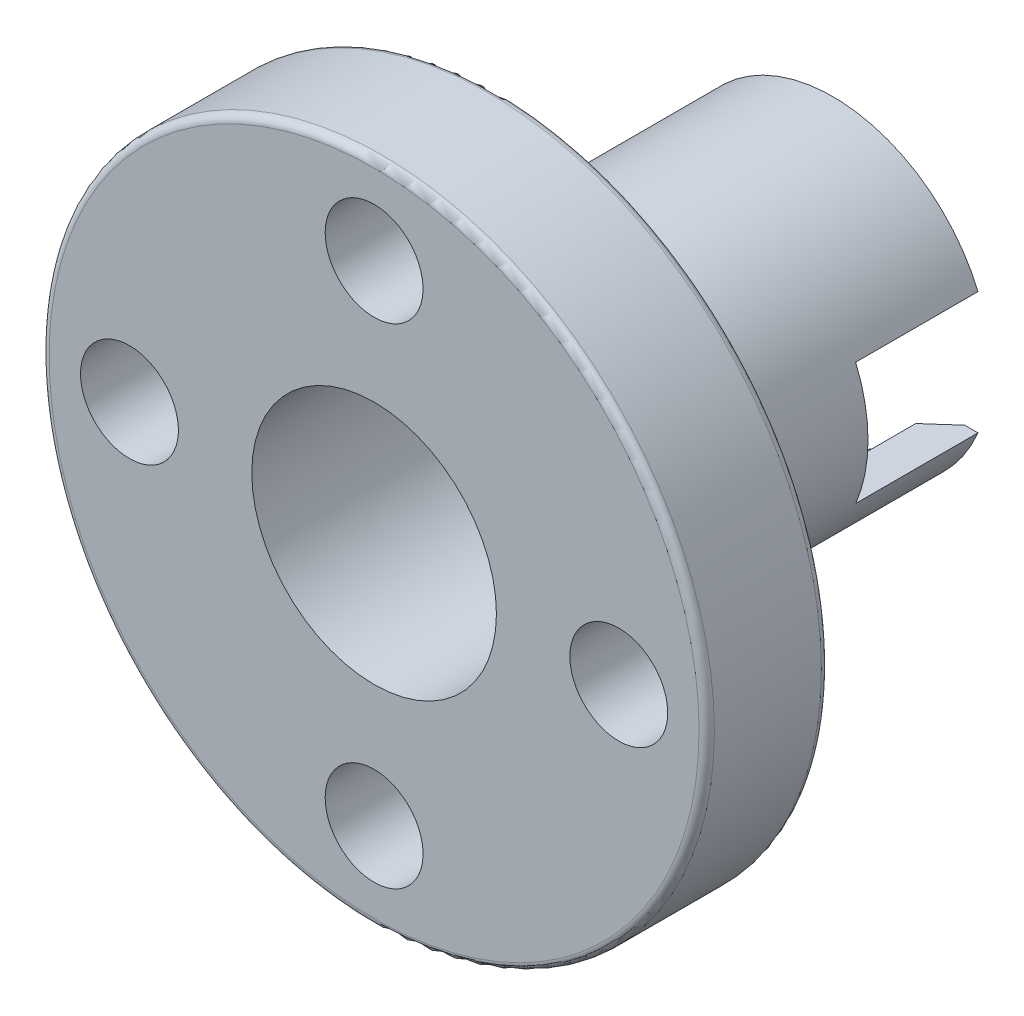
SolidWorks part; units mm, degrees
material "Brass"
ref_plane "Front Plane" through (0, 0, 0) normal (0, 0, 1) x (1, 0, 0)
ref_plane "Top Plane" through (0, 0, 0) normal (0, 1, 0) x (1, 0, 0)
ref_plane "Right Plane" through (0, 0, 0) normal (1, 0, 0) x (0, 0, -1)
sketch "Sketch1" plane through (0, 0, 0) normal (0, 1, 0) x (1, 0, 0)
  line L0 (0, 0) -> (-10.875, 0)
  line L1 (-10.875, 0) -> (-10.875, 4)
  line L2 (-10.875, 4) -> (-5.15, 4)
  line L3 (-5.15, 4) -> (-5.15, 15)
  line L4 (-5.15, 15) -> (0, 15)
  line L5 (0, 15) -> (0, 0)
  dimension "D1" = 10.875
  dimension "D2" = 5.15
  dimension "D3" = 4
  dimension "D4" = 15
revolve "Revolve1" add sketch "Sketch1" angle 360 about L5
sketch "Sketch2" plane through (0, 0, -15) normal (0, 0, -1) x (-1, 0, 0)
  circle A0 centre (0, 0) radius 4
extrude "Cut-Extrude1" cut sketch "Sketch2" against normal through all
sketch "Sketch3" plane through (0, 0, -4) normal (0, 0, -1) x (-1, 0, 0)
  line L0 (0, 0) -> (0, 8) construction
  circle A0 centre (0, 8) radius 1.6
  circle A1 centre (8, 0) radius 1.6
  circle A2 centre (0, -8) radius 1.6
  circle A3 centre (-8, 0) radius 1.6
  point P13 (0, 0)
  dimension "D2" = 3.2
  dimension "D1" = 8
  dimension "D3" = 4
extrude "Cut-Extrude2" cut sketch "Sketch3" against normal through all
ref_plane "Plane1" through (5.15, 0, 0) normal (1, 0, 0) x (0, 0, -1)
sketch "Sketch4" plane through (5.15, 0, 0) normal (1, 0, 0) x (0, 0, -1)
  line L0 (15, -5.15) -> (15, 5.15) construction
  line L1 (15, 2) -> (11, 2)
  line L2 (15, 2) -> (15, -2)
  line L3 (15, -2) -> (11, -2)
  line L4 (11, 2) -> (11, -2)
  point P6 (15, 0)
  dimension "D1" = 4
  dimension "D2" = 4
extrude "Cut-Extrude3" cut sketch "Sketch4" against normal through all
chamfer "Chamfer1" distance 0.75 angle 45 1 edges at (0, 4, -15)
chamfer "Chamfer2" distance 0.75 angle 45 1 edges at (0, -4, -15)
fillet "Fillet1" radius 0.5 1 edges at (-5.15, 0, -4)
fillet "Fillet2" radius 0.25 2 edges at (-10.875, 0, -4) (-10.875, 0, 0)
